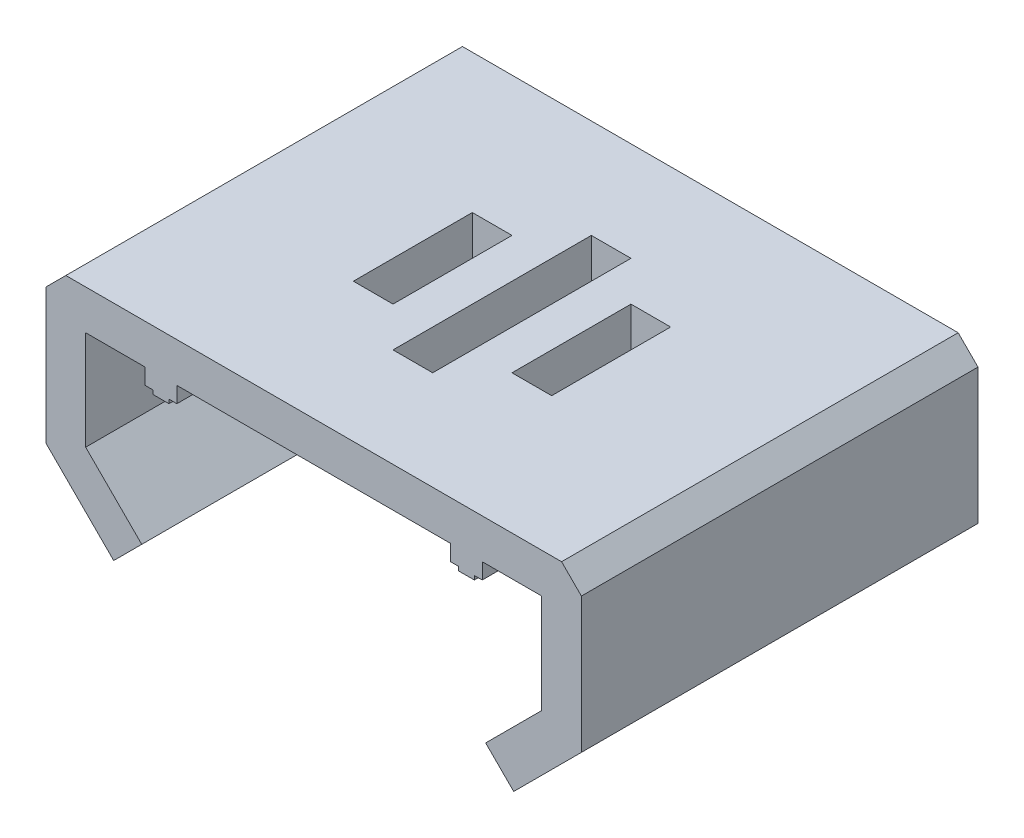
SolidWorks part; units mm, degrees
ref_plane "Front Plane" through (0, 0, 0) normal (0, 0, 1) x (1, 0, 0)
ref_plane "Top Plane" through (0, 0, 0) normal (0, 1, 0) x (1, 0, 0)
ref_plane "Right Plane" through (0, 0, 0) normal (1, 0, 0) x (0, 0, -1)
sketch "Sketch2" plane through (0, 0, 0) normal (0, 0, 1) x (1, 0, 0)
  line L0 (5.75, 0) -> (5.75, -2.5)
  line L5 (5.75, -2.5) -> (4.3358, -3.9142)
  line L6 (0, 0) -> (5.75, 0)
  line L14 (0, 1) -> (6.75, 1)
  line L15 (6.75, 1) -> (6.75, -2.9142)
  line L17 (6.75, -2.9142) -> (5.0429, -4.6213)
  line L18 (3.45, 0) -> (4.25, 0)
  line L19 (3.45, 0) -> (3.45, -0.4)
  line L20 (3.45, -0.4) -> (4.25, -0.4)
  line L21 (4.25, 0) -> (4.25, -0.4)
  line L22 (3.65, -0.4) -> (4.05, -0.4)
  line L23 (3.65, -0.4) -> (3.65, -0.5)
  line L24 (3.65, -0.5) -> (4.05, -0.5)
  line L25 (4.05, -0.4) -> (4.05, -0.5)
  line L26 (0, 1) -> (0, 0)
  line L27 (4.3358, -3.9142) -> (5.0429, -4.6213)
  arc A1 (4.3358, -3.9142) -> (5.0429, -4.6213) centre (4.6893, -4.2678) ccw
  point P16 (3.85, -0.4)
  point P21 (3.85, -0.4)
  dimension "D1" = 5.75
  dimension "D2" = 2.5
  dimension "D3" = 45
  dimension "D4" = 1.9
  dimension "D5" = 0.4
  dimension "D6" = 2
  dimension "D7" = 1
  dimension "D8" = 0.8
  dimension "D9" = 0.4
  dimension "D10" = 0.1
extrude "Boss-Extrude1" add sketch "Sketch2" along normal blind 10
mirror "Mirror1" about plane through (0, 0, 0) normal (1, 0, 0) of "Boss-Extrude1"
fillet "Fillet1" [suppressed] radius 0.5
chamfer "Chamfer1" distance 0.5 angle 45 2 edges at (6.75, 1, 5) (-6.75, 1, 5)
sketch "Sketch3" [suppressed] plane through (0, 0, 0) normal (0, -1, 0) x (1, 0, 0)
  line L0 (0, 10) -> (0, 0) construction
  line L2 (-3.45, 10) -> (3.45, 10) construction
  line L3 (-3.45, 0) -> (3.45, 0) construction
  line L4 (-0.5, 10) -> (0.5, 10) construction
  line L5 (-0.5, 10) -> (-0.5, 0) construction
  line L6 (-0.5, 0) -> (0.5, 0) construction
  line L7 (0.5, 10) -> (0.5, 0) construction
  line L8 (-0.5, 10) -> (0.5, 0) construction
  line L9 (-0.5, 0) -> (0.5, 10) construction
  line L10 (0.5, 7.5) -> (2, 7.5)
  line L11 (0.5, 7.5) -> (0.5, 2.5)
  line L12 (0.5, 2.5) -> (2, 2.5)
  line L13 (2, 7.5) -> (2, 2.5)
  point P5 (0, 5)
  point P16 (0.5, 5)
  point P17 (0.5, 5)
  dimension "D1" = 1
  dimension "D2" = 1.5
  dimension "D3" = 5
extrude "Boss-Extrude2" [suppressed] add sketch "Sketch3" along normal blind 1.5
sketch "Sketch4" [suppressed] plane through (0, -1.5, 0) normal (0, -1, 0) x (1, 0, 0)
  line L0 (2, 7.5) -> (0.5, 7.5) construction
  line L5 (0.25, 7.75) -> (2.25, 7.75)
  line L6 (0.25, 7.75) -> (0.25, 2.25)
  line L7 (0.25, 2.25) -> (2.25, 2.25)
  line L8 (2.25, 7.75) -> (2.25, 2.25)
  line L9 (0.25, 7.75) -> (2.25, 2.25) construction
  line L10 (0.25, 2.25) -> (2.25, 7.75) construction
  line L11 (0.5, 7.5) -> (0.5, 2.5) construction
  point P0 (1.25, 5)
  point P5 (0, 0)
  point P8 (1.25, 7.5)
  point P9 (0, 0)
  point P12 (0.5, 5)
  dimension "D1" = 2
  dimension "D2" = 5.5
extrude "Boss-Extrude3" [suppressed] add sketch "Sketch4" along normal blind 0.5
chamfer "Chamfer2" [suppressed] distance 0.25 angle 45
sketch "Sketch6" [suppressed] plane through (0, 0, 0) normal (0, 0, -1) x (-1, 0, 0)
  line L0 (0, 1) -> (0, -5.3509) construction
  line L1 (0.5, -1) -> (0, -1.5)
  line L2 (3.45, 0) -> (-3.45, 0) construction
  line L3 (-0.5, -1) -> (0.5, -1)
  line L4 (-0.5, -1) -> (-0.5, 0)
  line L5 (-0.5, 0) -> (0.5, 0)
  line L6 (0.5, -1) -> (0.5, 0)
  line L7 (-0.5, -1) -> (0.5, 0) construction
  line L8 (-0.5, 0) -> (0.5, -1) construction
  line L9 (0, -1.5) -> (0.5, -1.5)
  line L22 (0.5, 0) -> (1.5, 0)
  line L23 (0.5, 0) -> (0.5, -1.5)
  line L24 (0.5, -1.5) -> (1.5, -1.5)
  line L25 (1.5, 0) -> (1.5, -1.5)
  line L27 (1.5, -1.5) -> (2, -1.5)
  line L28 (2, -1.5) -> (1.5, -1)
  point P1 (0, -0.5)
  dimension "D1" = 1
  dimension "D2" = 1
  dimension "D3" = 1.5
  dimension "D4" = 1
  dimension "D5" = 0.5
extrude "Boss-Extrude4" [suppressed] add sketch "Sketch6" against normal up to surface (10 mm away)
sketch "Sketch7" plane through (0, 1, 0) normal (0, 1, 0) x (1, 0, 0)
  line L0 (0, 0) -> (0, -10) construction
  line L1 (-6.25, -10) -> (6.25, -10) construction
  line L2 (-6.25, -5) -> (6.25, -5) construction
  line L3 (-0.5, -3.5) -> (0.5, -3.5)
  line L4 (-0.5, -3.5) -> (-0.5, -6.5)
  line L5 (-0.5, -6.5) -> (0.5, -6.5)
  line L6 (0.5, -3.5) -> (0.5, -6.5)
  line L7 (-0.5, -3.5) -> (0.5, -6.5) construction
  line L8 (-0.5, -6.5) -> (0.5, -3.5) construction
  line L9 (-0.5, -3.5) -> (0.5, -3.5)
  line L10 (-0.5, -3.5) -> (-0.5, -2.5)
  line L11 (-0.5, -2.5) -> (0.5, -2.5)
  line L12 (0.5, -3.5) -> (0.5, -2.5)
  line L13 (-0.5, -6.5) -> (0.5, -6.5)
  line L14 (-0.5, -6.5) -> (-0.5, -7.5)
  line L15 (-0.5, -7.5) -> (0.5, -7.5)
  line L16 (0.5, -6.5) -> (0.5, -7.5)
  line L17 (-6.25, 0) -> (-6.25, -10) construction
  line L18 (6.25, -10) -> (6.25, 0) construction
  line L20 (-2.5, -3.5) -> (-1.5, -3.5)
  line L21 (-2.5, -3.5) -> (-2.5, -6.5)
  line L22 (-2.5, -6.5) -> (-1.5, -6.5)
  line L23 (-1.5, -3.5) -> (-1.5, -6.5)
  line L24 (-2.5, -3.5) -> (-1.5, -6.5) construction
  line L25 (-2.5, -6.5) -> (-1.5, -3.5) construction
  line L26 (2.5, -3.5) -> (1.5, -3.5)
  line L27 (2.5, -3.5) -> (2.5, -6.5)
  line L28 (2.5, -6.5) -> (1.5, -6.5)
  line L29 (1.5, -3.5) -> (1.5, -6.5)
  line L30 (2.5, -3.5) -> (1.5, -6.5) construction
  line L31 (2.5, -6.5) -> (1.5, -3.5) construction
  point P5 (0, -5)
  point P20 (-2, -5)
  point P25 (2, -5)
  dimension "D1" = 1
  dimension "D2" = 3
  dimension "D3" = 2
  dimension "D4" = 1
  dimension "D5" = 3
  dimension "D6" = 2
extrude "Cut-Extrude1" cut sketch "Sketch7" against normal through all contours L6 L3 L4 L5 | L3 L12 L11 L10 | L16 L5 L14 L15 | L26 L29 L28 L27 | L23 L20 L21 L22
